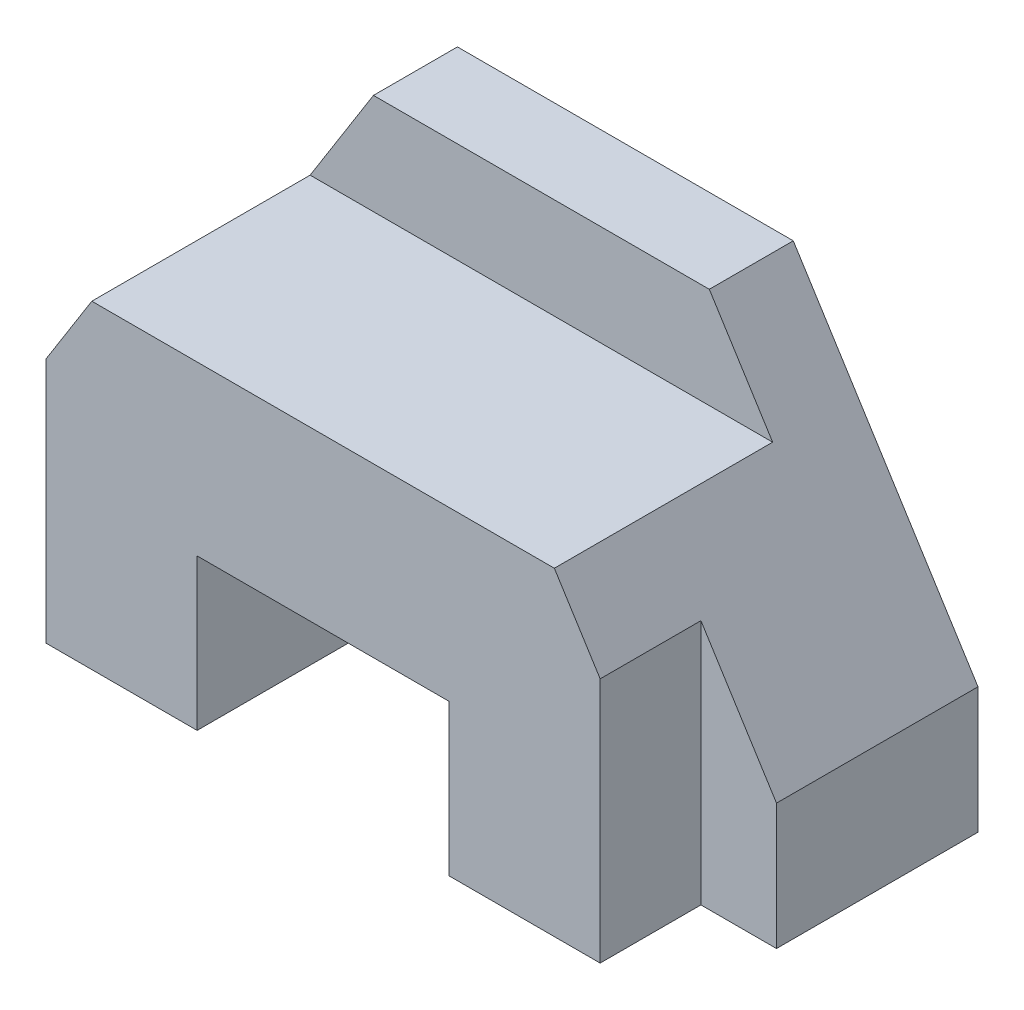
SolidWorks part; units mm, degrees
ref_plane "Alzado" through (0, 0, 0) normal (0, 0, 1) x (1, 0, 0)
ref_plane "Planta" through (0, 0, 0) normal (0, 1, 0) x (1, 0, 0)
ref_plane "Vista lateral" through (0, 0, 0) normal (1, 0, 0) x (0, 0, -1)
sketch "Croquis1" plane through (0, 0, 0) normal (0, 0, 1) x (1, 0, 0)
  line L0 (0, 40.8667) -> (0, -40.8667) construction
  line L1 (-42, -15) -> (42, -15)
  line L2 (42, -15) -> (42, 0)
  line L3 (42, 0) -> (20, 35)
  line L4 (20, 35) -> (-20, 35)
  line L5 (-42, 0) -> (-20, 35)
  line L6 (-42, -15) -> (-42, 0)
  point P0 (0, -40.8667)
  point P4 (0, 0)
  point P11 (0, 35)
  point P13 (0, -15)
  dimension "D1" = 84
  dimension "D2" = 50
  dimension "D3" = 15
  dimension "D4" = 40
extrude "Saliente-Extruir1" add sketch "Croquis1" along normal blind 36
sketch "Croquis2" plane through (0, 0, 36) normal (0, 0, 1) x (1, 0, 0)
  line L0 (-27.5429, 23) -> (27.5429, 23)
  line L1 (-20, 35) -> (-42, 0) construction
  line L2 (42, 0) -> (20, 35) construction
  line L9 (42, -15) -> (42, 0)
  line L10 (42, 0) -> (20, 35)
  line L11 (20, 35) -> (-20, 35)
  line L12 (-20, 35) -> (-42, 0)
  line L13 (-42, 0) -> (-42, -15)
  line L14 (-42, -15) -> (42, -15)
  line L15 (42, -15) -> (42, 0)
  line L16 (42, 0) -> (20, 35)
  line L17 (20, 35) -> (-20, 35)
  line L18 (-20, 35) -> (-42, 0)
  line L19 (-42, 0) -> (-42, -15)
  line L20 (-42, -15) -> (42, -15)
  line M2 (42, 0) -> (20, 35)
  line M3 (20, 35) -> (-20, 35)
  line M4 (-20, 35) -> (-42, 0)
  dimension "D1" = 0
  dimension "D2" = 38
extrude "Cortar-Extruir1" cut sketch "Croquis2" against normal blind 26 contours L0 M4 M2 M3
sketch "Croquis3" plane through (0, 0, 36) normal (0, 0, 1) x (1, 0, 0)
  line L0 (33, 14.3182) -> (33, -15)
  line L1 (42, 0) -> (27.5429, 23) construction
  line L2 (-42, -15) -> (42, -15) construction
  line L3 (-33, -15) -> (-33, 14.3182)
  line L4 (33, -15) -> (42, -15)
  line L9 (27.5429, 23) -> (-27.5429, 23)
  line L10 (-27.5429, 23) -> (-42, 0)
  line L11 (-42, 0) -> (-42, -15)
  line L12 (-42, -15) -> (42, -15)
  line L13 (42, -15) -> (42, 0)
  line L14 (42, 0) -> (27.5429, 23)
  line L16 (-33, 14.3182) -> (-42, 0)
  line L17 (-42, 0) -> (-42, -15)
  line L18 (-42, -15) -> (-33, -15)
  line L19 (42, -15) -> (42, 0)
  line L20 (42, 0) -> (33, 14.3182)
  dimension "D1" = 0
  dimension "D2" = 66
extrude "Cortar-Extruir2" cut sketch "Croquis3" against normal blind 12
sketch "Croquis4" plane through (0, 0, 36) normal (0, 0, 1) x (1, 0, 0)
  line L0 (-33, -15) -> (33, -15) construction
  line L1 (-15, -15) -> (15, -15)
  line L2 (-15, -15) -> (-15, 3)
  line L3 (-15, 3) -> (15, 3)
  line L4 (15, -15) -> (15, 3)
  point P6 (0, -15)
  dimension "D2" = 30
  dimension "D3" = 18
extrude "Cortar-Extruir3" cut sketch "Croquis4" against normal through all
